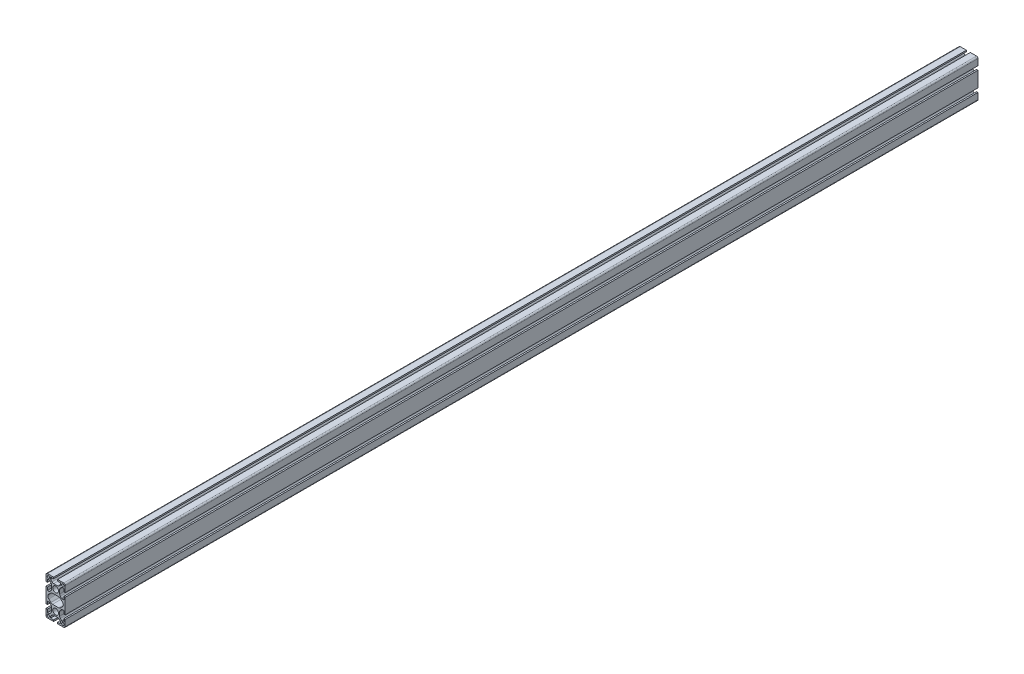
SolidWorks part; units mm, degrees
ref_plane "Front Plane" through (0, 0, 0) normal (0, 0, 1) x (1, 0, 0)
ref_plane "Top Plane" through (0, 0, 0) normal (0, 1, 0) x (1, 0, 0)
ref_plane "Right Plane" through (0, 0, 0) normal (1, 0, 0) x (0, 0, -1)
sketch "Sketch1" plane through (0, 0, 0) normal (0, 0, 1) x (1, 0, 0)
  line L0 (-17, -40) -> (-4.1, -40)
  line L1 (-4.1, -40) -> (-4.1, -37)
  line L2 (-4.1, -37) -> (-10.5, -37)
  line L3 (-10.5, -37) -> (-10.5, -33.6627)
  line L4 (-10.0314, -32.5314) -> (-7.4645, -29.9645)
  line L5 (-3.9289, -28.5) -> (3.9289, -28.5)
  line L6 (7.4645, -29.9645) -> (10.0314, -32.5314)
  line L7 (10.5, -33.6627) -> (10.5, -37)
  line L8 (10.5, -37) -> (4.1, -37)
  line L9 (4.1, -37) -> (4.1, -40)
  line L10 (4.1, -40) -> (17, -40)
  line L11 (20, -37) -> (20, -24.1)
  line L12 (20, -24.1) -> (17, -24.1)
  line L13 (17, -24.1) -> (17, -30.5)
  line L14 (17, -30.5) -> (13.6627, -30.5)
  line L15 (12.5314, -30.0314) -> (9.9645, -27.4645)
  line L16 (8.5, -23.9289) -> (8.5, -16.0711)
  line L17 (9.9645, -12.5355) -> (12.5314, -9.9686)
  line L18 (13.6627, -9.5) -> (17, -9.5)
  line L19 (17, -9.5) -> (17, -15.9)
  line L20 (17, -15.9) -> (20, -15.9)
  line L21 (20, -15.9) -> (20, 15.9)
  line L22 (20, 15.9) -> (17, 15.9)
  line L23 (17, 15.9) -> (17, 9.5)
  line L24 (17, 9.5) -> (13.6627, 9.5)
  line L25 (12.5314, 9.9686) -> (9.9645, 12.5355)
  line L26 (8.5, 16.0711) -> (8.5, 23.9289)
  line L27 (9.9645, 27.4645) -> (12.5314, 30.0314)
  line L28 (13.6627, 30.5) -> (17, 30.5)
  line L29 (17, 30.5) -> (17, 24.1)
  line L30 (17, 24.1) -> (20, 24.1)
  line L31 (20, 24.1) -> (20, 37)
  line L32 (17, 40) -> (4.1, 40)
  line L33 (4.1, 40) -> (4.1, 37)
  line L34 (4.1, 37) -> (10.5, 37)
  line L35 (10.5, 37) -> (10.5, 33.6627)
  line L36 (10.0314, 32.5314) -> (7.4645, 29.9645)
  line L37 (3.9289, 28.5) -> (-3.9289, 28.5)
  line L38 (-7.4645, 29.9645) -> (-10.0314, 32.5314)
  line L39 (-10.5, 33.6627) -> (-10.5, 37)
  line L40 (-10.5, 37) -> (-4.1, 37)
  line L41 (-4.1, 37) -> (-4.1, 40)
  line L42 (-4.1, 40) -> (-17, 40)
  line L43 (-20, 37) -> (-20, 24.1)
  line L44 (-20, 24.1) -> (-17, 24.1)
  line L45 (-17, 24.1) -> (-17, 30.5)
  line L46 (-17, 30.5) -> (-13.6627, 30.5)
  line L47 (-12.5314, 30.0314) -> (-9.9645, 27.4645)
  line L48 (-8.5, 23.9289) -> (-8.5, 16.0711)
  line L49 (-9.9645, 12.5355) -> (-12.5314, 9.9686)
  line L50 (-13.6627, 9.5) -> (-17, 9.5)
  line L51 (-17, 9.5) -> (-17, 15.9)
  line L52 (-17, 15.9) -> (-20, 15.9)
  line L53 (-20, 15.9) -> (-20, -15.9)
  line L54 (-20, -15.9) -> (-17, -15.9)
  line L55 (-17, -15.9) -> (-17, -9.5)
  line L56 (-17, -9.5) -> (-13.6627, -9.5)
  line L57 (-12.5314, -9.9686) -> (-9.9645, -12.5355)
  line L58 (-8.5, -16.0711) -> (-8.5, -23.9289)
  line L59 (-9.9645, -27.4645) -> (-12.5314, -30.0314)
  line L60 (-13.6627, -30.5) -> (-17, -30.5)
  line L61 (-17, -30.5) -> (-17, -24.1)
  line L62 (-17, -24.1) -> (-20, -24.1)
  line L63 (-20, -24.1) -> (-20, -37)
  line L64 (-14.2426, -4.2426) -> (-9.9497, -8.5355)
  line L65 (-6.4142, -10) -> (6.4142, -10)
  line L66 (9.9497, -8.5355) -> (14.2426, -4.2426)
  line L67 (14.2426, 4.2426) -> (9.9497, 8.5355)
  line L68 (6.4142, 10) -> (-6.4142, 10)
  line L69 (-9.9497, 8.5355) -> (-14.2426, 4.2426)
  arc A0 (-20, -37) -> (-17, -40) centre (-17, -37) ccw
  arc A1 (-10.5, -33.6627) -> (-10.0314, -32.5314) centre (-8.9, -33.6627) cw
  arc A2 (-7.4645, -29.9645) -> (-3.9289, -28.5) centre (-3.9289, -33.5) cw
  arc A3 (3.9289, -28.5) -> (7.4645, -29.9645) centre (3.9289, -33.5) cw
  arc A4 (10.0314, -32.5314) -> (10.5, -33.6627) centre (8.9, -33.6627) cw
  arc A5 (17, -40) -> (20, -37) centre (17, -37) ccw
  arc A6 (13.6627, -30.5) -> (12.5314, -30.0314) centre (13.6627, -28.9) cw
  arc A7 (9.9645, -27.4645) -> (8.5, -23.9289) centre (13.5, -23.9289) cw
  arc A8 (8.5, -16.0711) -> (9.9645, -12.5355) centre (13.5, -16.0711) cw
  arc A9 (12.5314, -9.9686) -> (13.6627, -9.5) centre (13.6627, -11.1) cw
  arc A10 (13.6627, 9.5) -> (12.5314, 9.9686) centre (13.6627, 11.1) cw
  arc A11 (9.9645, 12.5355) -> (8.5, 16.0711) centre (13.5, 16.0711) cw
  arc A12 (8.5, 23.9289) -> (9.9645, 27.4645) centre (13.5, 23.9289) cw
  arc A13 (12.5314, 30.0314) -> (13.6627, 30.5) centre (13.6627, 28.9) cw
  arc A14 (20, 37) -> (17, 40) centre (17, 37) ccw
  arc A15 (10.5, 33.6627) -> (10.0314, 32.5314) centre (8.9, 33.6627) cw
  arc A16 (7.4645, 29.9645) -> (3.9289, 28.5) centre (3.9289, 33.5) cw
  arc A17 (-3.9289, 28.5) -> (-7.4645, 29.9645) centre (-3.9289, 33.5) cw
  arc A18 (-10.0314, 32.5314) -> (-10.5, 33.6627) centre (-8.9, 33.6627) cw
  arc A19 (-17, 40) -> (-20, 37) centre (-17, 37) ccw
  arc A20 (-13.6627, 30.5) -> (-12.5314, 30.0314) centre (-13.6627, 28.9) cw
  arc A21 (-9.9645, 27.4645) -> (-8.5, 23.9289) centre (-13.5, 23.9289) cw
  arc A22 (-8.5, 16.0711) -> (-9.9645, 12.5355) centre (-13.5, 16.0711) cw
  arc A23 (-12.5314, 9.9686) -> (-13.6627, 9.5) centre (-13.6627, 11.1) cw
  arc A24 (-13.6627, -9.5) -> (-12.5314, -9.9686) centre (-13.6627, -11.1) cw
  arc A25 (-9.9645, -12.5355) -> (-8.5, -16.0711) centre (-13.5, -16.0711) cw
  arc A26 (-8.5, -23.9289) -> (-9.9645, -27.4645) centre (-13.5, -23.9289) cw
  arc A27 (-12.5314, -30.0314) -> (-13.6627, -30.5) centre (-13.6627, -28.9) cw
  circle A28 centre (15, 35) radius 2.5
  circle A29 centre (15, -35) radius 2.5
  circle A30 centre (0, 20) radius 6
  circle A31 centre (0, -20) radius 6
  arc A32 (-14.2426, 4.2426) -> (-14.2426, -4.2426) centre (-10, 0) ccw
  arc A33 (-9.9497, -8.5355) -> (-6.4142, -10) centre (-6.4142, -5) ccw
  arc A34 (6.4142, -10) -> (9.9497, -8.5355) centre (6.4142, -5) ccw
  arc A35 (14.2426, -4.2426) -> (14.2426, 4.2426) centre (10, 0) ccw
  arc A36 (9.9497, 8.5355) -> (6.4142, 10) centre (6.4142, 5) ccw
  arc A37 (-6.4142, 10) -> (-9.9497, 8.5355) centre (-6.4142, 5) ccw
  circle A38 centre (-15, 35) radius 2.5
  circle A39 centre (-15, -35) radius 2.5
  dimension "D1" = 40
  dimension "D2" = 80
extrude "Boss-Extrude1" add sketch "Sketch1" against normal blind 1900
